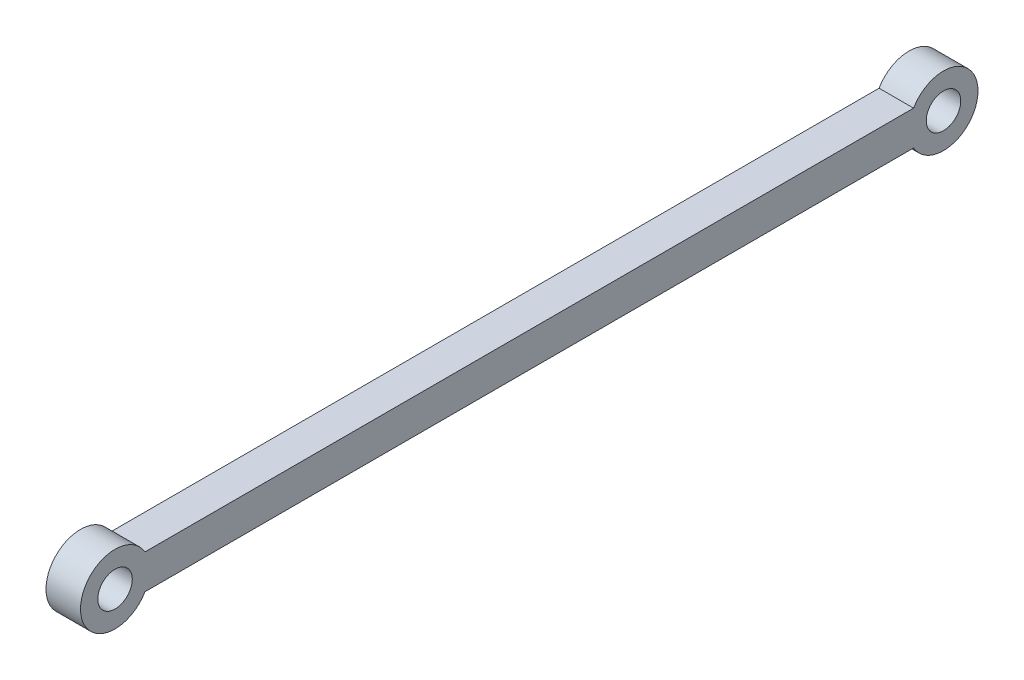
SolidWorks part; units mm, degrees
ref_plane "정면" through (0, 0, 0) normal (0, 0, 1) x (1, 0, 0)
ref_plane "윗면" through (0, 0, 0) normal (0, 1, 0) x (1, 0, 0)
ref_plane "우측면" through (0, 0, 0) normal (1, 0, 0) x (0, 0, -1)
sketch "스케치1" plane through (0, 0, 0) normal (1, 0, 0) x (0, 0, -1)
  line L0 (-30, 0) -> (30, 0) construction
  line L1 (-27.8349, 1.25) -> (27.8349, 1.25)
  line L3 (-27.8349, -1.25) -> (27.8349, -1.25)
  line L5 (0, 1.25) -> (0, -1.25) construction
  arc A0 (-27.8349, 1.25) -> (-27.8349, -1.25) centre (-30, 0) ccw
  circle A1 centre (-30, 0) radius 1.25
  arc A2 (27.8349, -1.25) -> (27.8349, 1.25) centre (30, 0) ccw
  circle A3 centre (30, 0) radius 1.25
  dimension "D3" = 5
  dimension "D4" = 5
  dimension "D1" = 2.5
  dimension "D2" = 60
extrude "보스-돌출1" add sketch "스케치1" along normal blind 2.5
equation "\"link11\" = 80"
equation "\"link12\" = 40"
equation "\"link21\"= 60"
equation "\"link22\"= 40"
equation "\"link31\"= 50"
equation "\"link32\"= 40"
equation "\"link41\"= 40"
equation "\"link42\"= 40"
equation "\"D2@스케치1\"=\"link21\""
